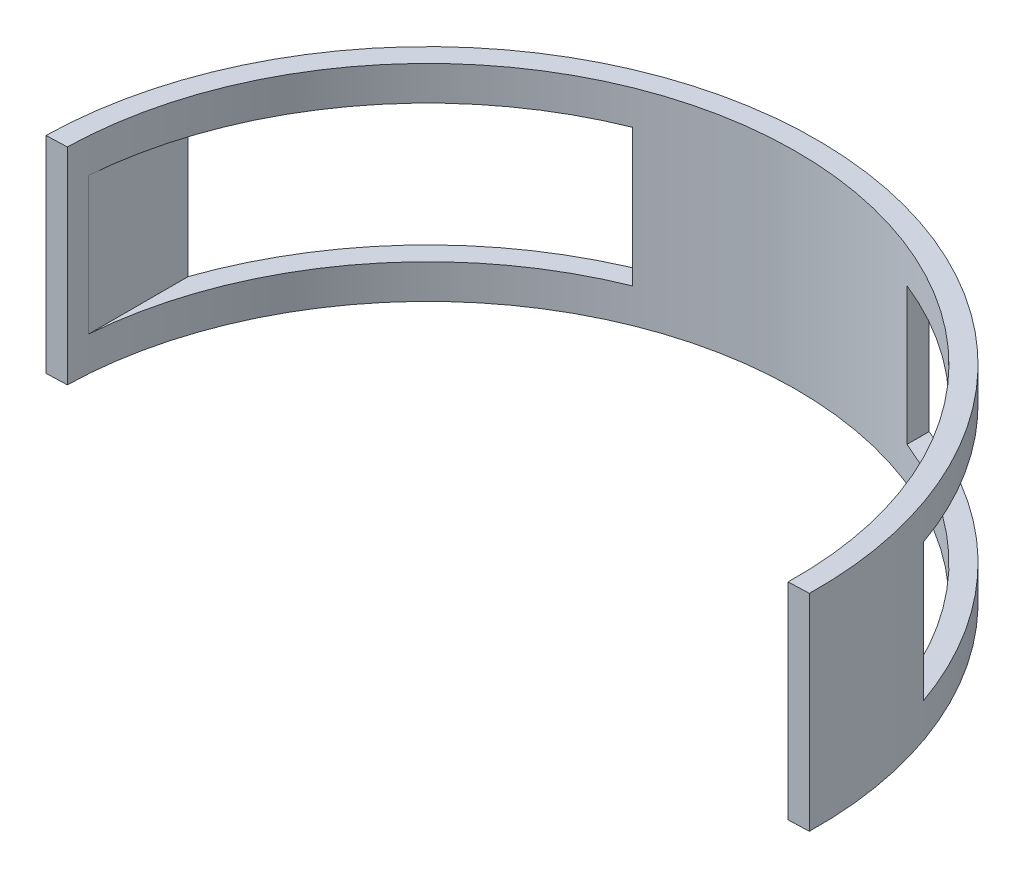
SolidWorks part; units mm, degrees
ref_plane "Front Plane" through (0, 0, 0) normal (0, 0, 1) x (1, 0, 0)
ref_plane "Top Plane" through (0, 0, 0) normal (0, 1, 0) x (1, 0, 0)
ref_plane "Right Plane" through (0, 0, 0) normal (1, 0, 0) x (0, 0, -1)
sketch "Sketch1" plane through (0, 0, 0) normal (0, 1, 0) x (1, 0, 0)
  line L0 (-56.6451, 1.0852) -> (-53.6469, 1.1868)
  line L1 (53.6469, -1.1868) -> (56.6451, -1.0849)
  arc A0 (56.6451, -1.0849) -> (-56.6451, 1.0852) centre (0, 0) ccw
  arc A1 (53.6469, -1.1868) -> (-53.6469, 1.1868) centre (0, 0) ccw
extrude "Boss-Extrude1" add sketch "Sketch1" along normal mid plane 30
sketch "Sketch3" plane through (0, 0, 0) normal (0, 0, 1) x (1, 0, 0)
  line L5 (-53.5, -10) -> (53.5, 10) construction
  line L6 (-53.5, 10) -> (53.5, -10) construction
  line L8 (-19.9755, -15) -> (19.9755, -15)
  line L9 (-19.9755, -15) -> (-19.9755, 15)
  line L10 (-19.9755, 15) -> (19.9755, 15)
  line L11 (19.9755, -15) -> (19.9755, 15)
  line L12 (-19.9755, -15) -> (19.9755, 15) construction
  line L13 (-19.9755, 15) -> (19.9755, -15) construction
  line L14 (53.66, 15) -> (-53.6469, 15) construction
  line L16 (-53.5, -10) -> (53.5, -10)
  line L17 (-53.5, -10) -> (-53.5, 10)
  line L18 (-53.5, 10) -> (53.5, 10)
  line L19 (53.5, -10) -> (53.5, 10)
  line L20 (-53.5, -10) -> (53.5, 10) construction
  line L21 (-53.5, 10) -> (53.5, -10) construction
  point P0 (0, 0)
  point P6 (0, 0)
  point P13 (0, 0)
sketch "Sketch4" plane through (0, 0, 0) normal (0, 0, 1) x (1, 0, 0)
  line L0 (-53.5, 10) -> (-19.9755, 10)
  line L1 (-19.9755, -15) -> (-19.9755, 15) construction
  line L2 (-53.5, 10) -> (53.5, 10) construction
  line L3 (-19.9755, 10) -> (-19.9755, -10)
  line L4 (-53.5, -10) -> (53.5, -10) construction
  line L5 (-19.9755, -10) -> (-53.5, -10)
  line L6 (-53.5, -10) -> (-53.5, 10)
  line L7 (53.5, 10) -> (53.5, -10)
  line L8 (53.5, -10) -> (19.9755, -10)
  line L9 (19.9755, -15) -> (19.9755, 15) construction
  line L10 (19.9755, -10) -> (19.9755, 10)
  line L11 (19.9755, 10) -> (53.5, 10)
extrude "Cut-Extrude2" cut sketch "Sketch4" against normal blind 200
